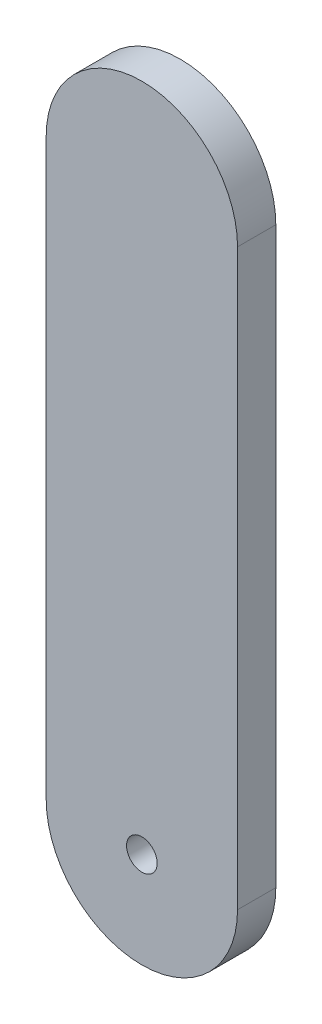
SolidWorks part; units mm, degrees
ref_plane "Front Plane" through (0, 0, 0) normal (0, 0, 1) x (1, 0, 0)
ref_plane "Top Plane" through (0, 0, 0) normal (0, 1, 0) x (1, 0, 0)
ref_plane "Right Plane" through (0, 0, 0) normal (1, 0, 0) x (0, 0, -1)
sketch "Sketch2" plane through (0, 0, 0) normal (0, 0, 1) x (1, 0, 0)
  line L2 (25, 0) -> (25, 150)
  line L4 (-25, 0) -> (-25, 150)
  arc A0 (25, 150) -> (-25, 150) centre (0, 150) ccw
  arc A4 (-25, 0) -> (25, 0) centre (0, 0) ccw
  point P0 (0, 0)
  dimension "D1" = 150
  dimension "D2" = 50
extrude "Boss-Extrude1" add sketch "Sketch2" along normal blind 10
sketch "Sketch3" plane through (0, 0, 0) normal (0, 0, -1) x (-1, 0, 0)
  circle A1 centre (0, 0) radius 4
extrude "Cut-Extrude1" cut sketch "Sketch3" against normal blind 10
